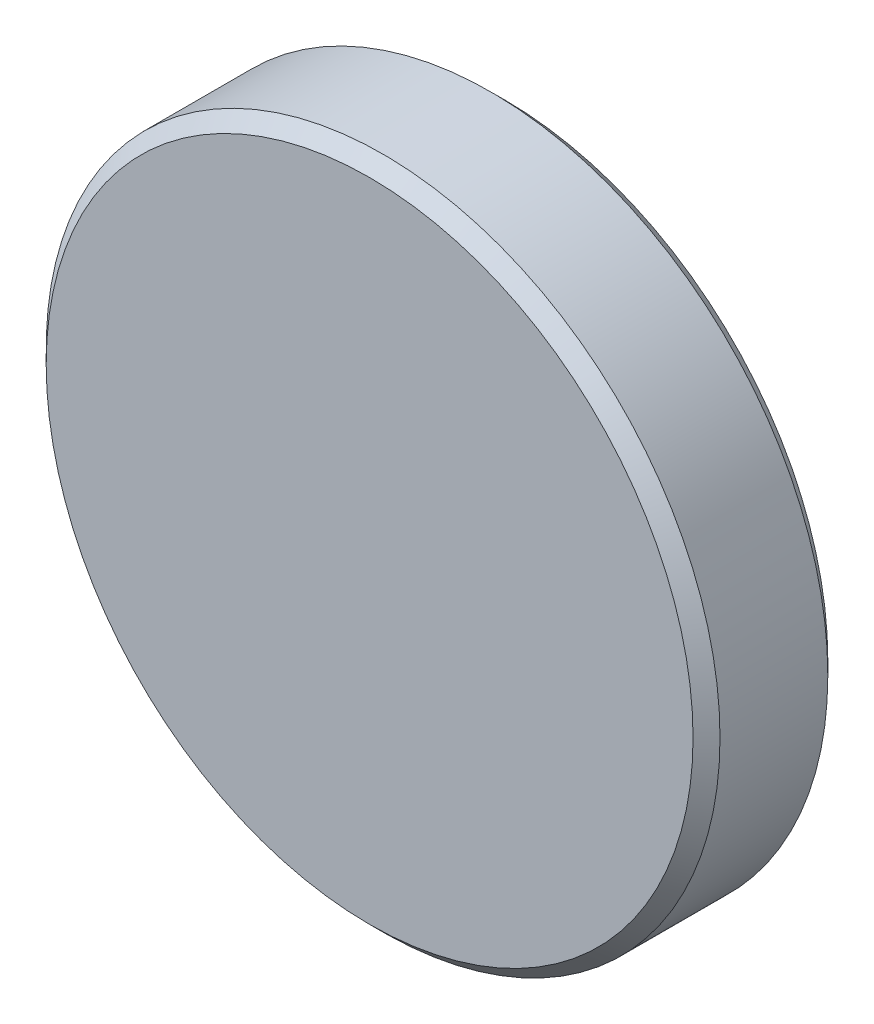
SolidWorks part; units mm, degrees
ref_plane "Front Plane" through (0, 0, 0) normal (0, 0, 1) x (1, 0, 0)
ref_plane "Top Plane" through (0, 0, 0) normal (0, 1, 0) x (1, 0, 0)
ref_plane "Right Plane" through (0, 0, 0) normal (1, 0, 0) x (0, 0, -1)
sketch "Sketch1" plane through (0, 0, 0) normal (0, 0, 1) x (1, 0, 0)
  circle A0 centre (0, 0) radius 2.5
  dimension "D1" = 5
extrude "Boss-Extrude1" add sketch "Sketch1" along normal blind 1
chamfer "Chamfer1" distance 0.1 angle 45 2 edges at (2.5, 0, 0) (2.5, 0, 1)
